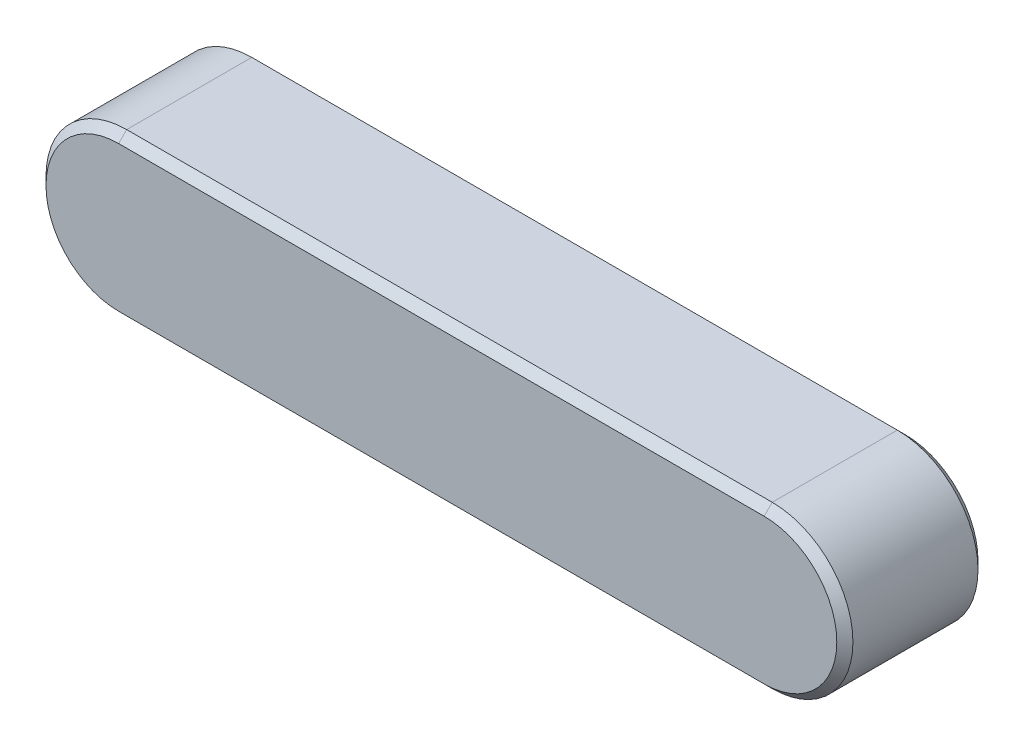
SolidWorks part; units mm, degrees
ref_plane "Front" through (0, 0, 0) normal (0, 0, 1) x (1, 0, 0)
ref_plane "Top" through (0, 0, 0) normal (0, 1, 0) x (1, 0, 0)
ref_plane "Right" through (0, 0, 0) normal (1, 0, 0) x (0, 0, -1)
sketch "Sketch1" plane through (0, 0, 0) normal (0, 0, 1) x (1, 0, 0)
  line L0 (-32, 4) -> (0, 4)
  line L1 (0, -4) -> (-32, -4)
  arc A0 (0, 4) -> (0, -4) centre (0, 0) cw
  arc A1 (-32, -4) -> (-32, 4) centre (-32, 0) cw
  dimension "L" = 40
  dimension "b" = 8
extrude "BaseKey" add sketch "Sketch1" along normal mid plane 7
sketch "Sketch2" plane through (0, 0, 0) normal (0, 0, 1) x (1, 0, 0)
  line L1 (-36, 4) -> (4, 4)
  line L2 (-36, 4) -> (-36, -4)
  line L3 (-36, -4) -> (4, -4)
  line L4 (4, 4) -> (4, -4)
  line L6 (0, -4) -> (-32, -4) construction
  line L7 (-32, 4) -> (0, 4) construction
  arc A2 (0, -4) -> (0, 4) centre (0, 0) ccw construction
  arc A3 (-32, 4) -> (-32, -4) centre (-32, 0) ccw construction
extrude "Extrude1" [suppressed] add sketch "Sketch2" along normal mid plane 7
sketch "Sketch3" plane through (0, 0, 0) normal (0, 0, 1) x (1, 0, 0)
  line L0 (4, 4) -> (-32, 4)
  line L1 (-32, -4) -> (4, -4)
  line L2 (4, -4) -> (4, 4)
  line L5 (-32, 4) -> (0, 4) construction
  arc A0 (-32, 4) -> (-32, -4) centre (-32, 0) ccw
  arc A1 (0, -4) -> (0, 4) centre (0, 0) ccw construction
  arc A4 (-32, 4) -> (-32, -4) centre (-32, 0) ccw construction
extrude "Extrude2" [suppressed] add sketch "Sketch3" along normal mid plane 7
chamfer "Chamfer1" distance 0.4 angle 45 8 edges at (4, 0, -3.5) (-16, -4, -3.5) (-36, 0, -3.5) (-16, 4, -3.5) (-36, 0, 3.5) (-16, -4, 3.5) (4, 0, 3.5) (-16, 4, 3.5)
equation "\"D1@Extrude1\"=\"h@BaseKey\""
equation "\"D1@Extrude2\"=\"h@BaseKey\""
